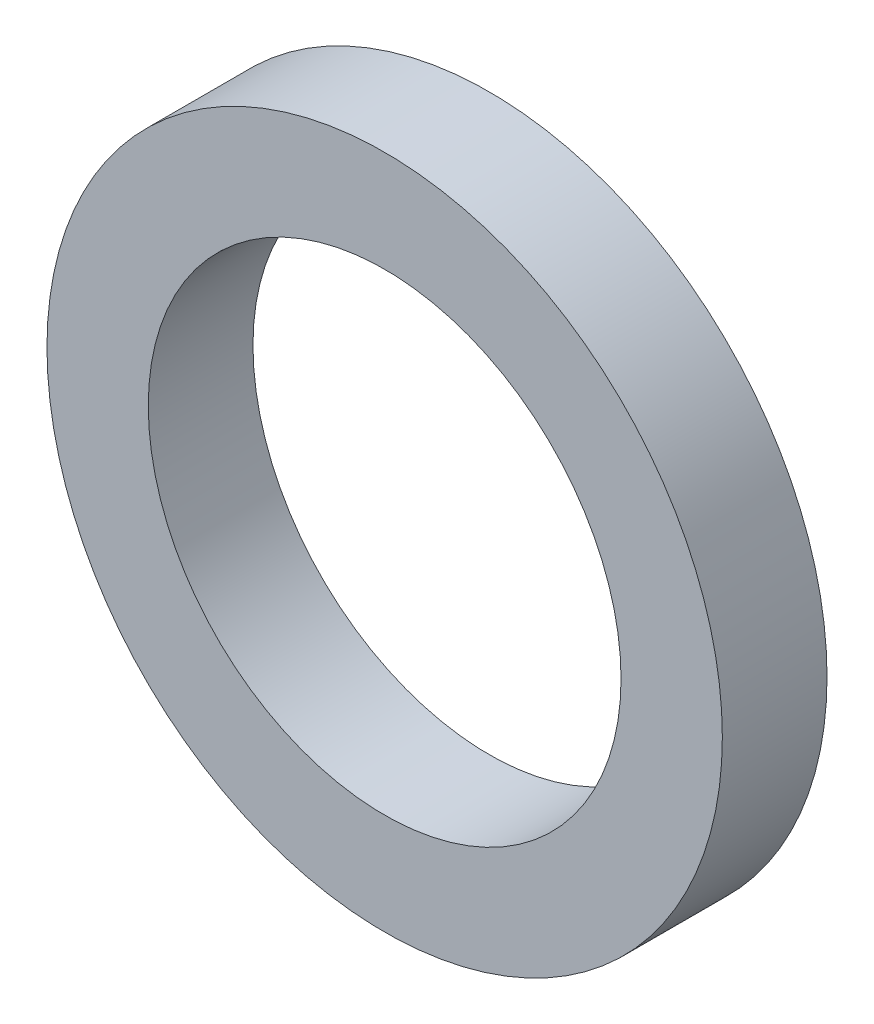
SolidWorks part; units mm, degrees
material "S45C"
ref_plane "Front Plane" through (0, 0, 0) normal (0, 0, 1) x (1, 0, 0)
ref_plane "Top Plane" through (0, 0, 0) normal (0, 1, 0) x (1, 0, 0)
ref_plane "Right Plane" through (0, 0, 0) normal (1, 0, 0) x (0, 0, -1)
sketch "Sketch1" plane through (0, 0, 0) normal (0, 0, 1) x (1, 0, 0)
  circle A0 centre (0, 0) radius 14
  circle A1 centre (0, 0) radius 20
  dimension "D1" = 28
  dimension "D2" = 40
extrude "Boss-Extrude1" add sketch "Sketch1" along normal mid plane 6.2
